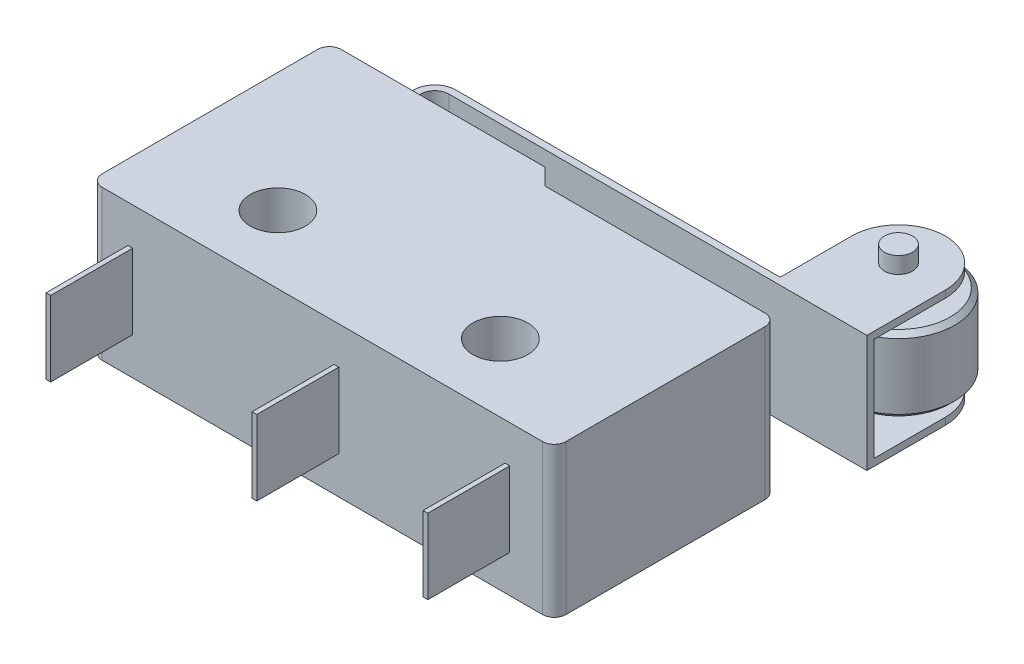
SolidWorks part; units mm, degrees
ref_plane "前视基准面" through (0, 0, 0) normal (0, 0, 1) x (1, 0, 0)
ref_plane "上视基准面" through (0, 0, 0) normal (0, 1, 0) x (1, 0, 0)
ref_plane "右视基准面" through (0, 0, 0) normal (1, 0, 0) x (0, 0, -1)
sketch "草图1" plane through (0, 0, 0) normal (0, 1, 0) x (1, 0, 0)
  line L0 (9.9, 4.4) -> (0, 4.4)
  line L1 (-9.9, 5.1) -> (-0.7, 5.1)
  line L2 (-9.9, 5.1) -> (-9.9, -5.1)
  line L3 (-9.9, -5.1) -> (9.9, -5.1)
  line L4 (9.9, 4.4) -> (9.9, -5.1)
  line L5 (-9.9, 5.1) -> (9.9, -5.1) construction
  line L6 (-9.9, -5.1) -> (9.9, 5.1) construction
  line L7 (0, 4.4) -> (-0.7, 5.1)
  point P0 (0, 0)
  dimension "D1" = 10.2
  dimension "D2" = 19.8
  dimension "D3" = 225
  dimension "D4" = 9.5
  dimension "D5" = 5.1
extrude "凸台-拉伸1" add sketch "草图1" along normal mid plane 6.4
sketch "草图2" plane through (0, 3.2, 0) normal (0, 1, 0) x (1, 0, 0)
  line L0 (-9.9, -5.1) -> (9.9, -5.1) construction
  line L1 (-9.9, 5.1) -> (-9.9, -5.1) construction
  circle A0 centre (-4.8, -2.2) radius 1.175
  circle A1 centre (4.7, -2.2) radius 1.175
  dimension "D4" = 2.35
  dimension "D5" = 2.35
  dimension "D1" = 2.9
  dimension "D2" = 5.1
  dimension "D3" = 9.5
extrude "切除-拉伸1" cut sketch "草图2" against normal up to next
fillet "圆角1" radius 0.5 4 edges at (9.9, 0, -4.4) (9.9, 0, 5.1) (-9.9, 0, 5.1) (-9.9, 0, -5.1)
sketch "草图3" plane through (0, 0, 0) normal (0, 1, 0) x (1, 0, 0)
  line L0 (-6.9, 5.1) -> (-6.9, 5.85)
  line L1 (-0.7, 5.1) -> (-9.4, 5.1) construction
  line L2 (-6.15, 6.6) -> (11.7, 6.6)
  line L3 (-9.9, 4.6) -> (-9.9, -4.6) construction
  circle A0 centre (-4.8, -2.2) radius 1.175 construction
  arc A1 (-6.9, 5.85) -> (-6.15, 6.6) centre (-6.15, 5.85) cw
  point P11 (-6.9, 6.6)
  dimension "D4" = 0.75
  dimension "D1" = 16.5
  dimension "D2" = 1.5
  dimension "D3" = 3
extrude "拉伸-薄壁1" add sketch "草图3" along normal mid plane 5 thin thin type two direction wall 0.15 second wall 0.15
sketch "草图4" plane through (0, 2.5, 0) normal (0, 1, 0) x (1, 0, 0)
  line L0 (7.7, 9.8) -> (7.7, 6.45)
  line L1 (-6.15, 6.45) -> (11.7, 6.45) construction
  line L2 (7.7, 6.45) -> (11.7, 6.45)
  line L3 (11.7, 6.45) -> (11.7, 9.8)
  arc A0 (11.7, 9.8) -> (7.7, 9.8) centre (9.7, 9.8) ccw
  circle A1 centre (4.7, -2.2) radius 1.175 construction
  circle A2 centre (-4.8, -2.2) radius 1.175 construction
  dimension "D1" = 4
  dimension "D2" = 12
  dimension "D3" = 14.5
extrude "凸台-拉伸2" add sketch "草图4" against normal blind 0.3
mirror "镜向1" about plane through (0, 0, 0) normal (0, 1, 0) of "凸台-拉伸2"
sketch "草图5" plane through (0, 3.2, 0) normal (0, 1, 0) x (1, 0, 0)
  circle A0 centre (9.7, 9.8) radius 0.6
  dimension "D1" = 1.2
extrude "凸台-拉伸3" add sketch "草图5" against normal up to surface (6.4 mm away) up to face at (4.7, -3.2, 3.375)
sketch "草图6" plane through (0, 0, 0) normal (0, 1, 0) x (1, 0, 0)
  circle A0 centre (9.7, 9.8) radius 2.4
  dimension "D1" = 4.8
extrude "凸台-拉伸4" add sketch "草图6" along normal mid plane 3.2
chamfer "倒角1" distance 0.2 angle 45 2 edges at (9.7, -1.6, -7.4) (9.7, 1.6, -7.4)
sketch "草图7" plane through (0, 0, 0) normal (0, 1, 0) x (1, 0, 0)
  line L0 (-8.3, -5.1) -> (-8.3, -8.6)
  line L1 (-9.4, -5.1) -> (9.4, -5.1) construction
  line L2 (0.5, -5.1) -> (0.5, -8.6)
  line L3 (7.8, -5.1) -> (7.8, -8.6)
  line L4 (-9.9, 4.6) -> (-9.9, -4.6) construction
  circle A0 centre (-4.8, -2.2) radius 1.175 construction
  dimension "D1" = 6.4
  dimension "D2" = 1.6
  dimension "D3" = 8.8
  dimension "D4" = 7.3
extrude "拉伸-薄壁2" add sketch "草图7" along normal mid plane 3.2 thin thin type one direction reverse wall 0.2
